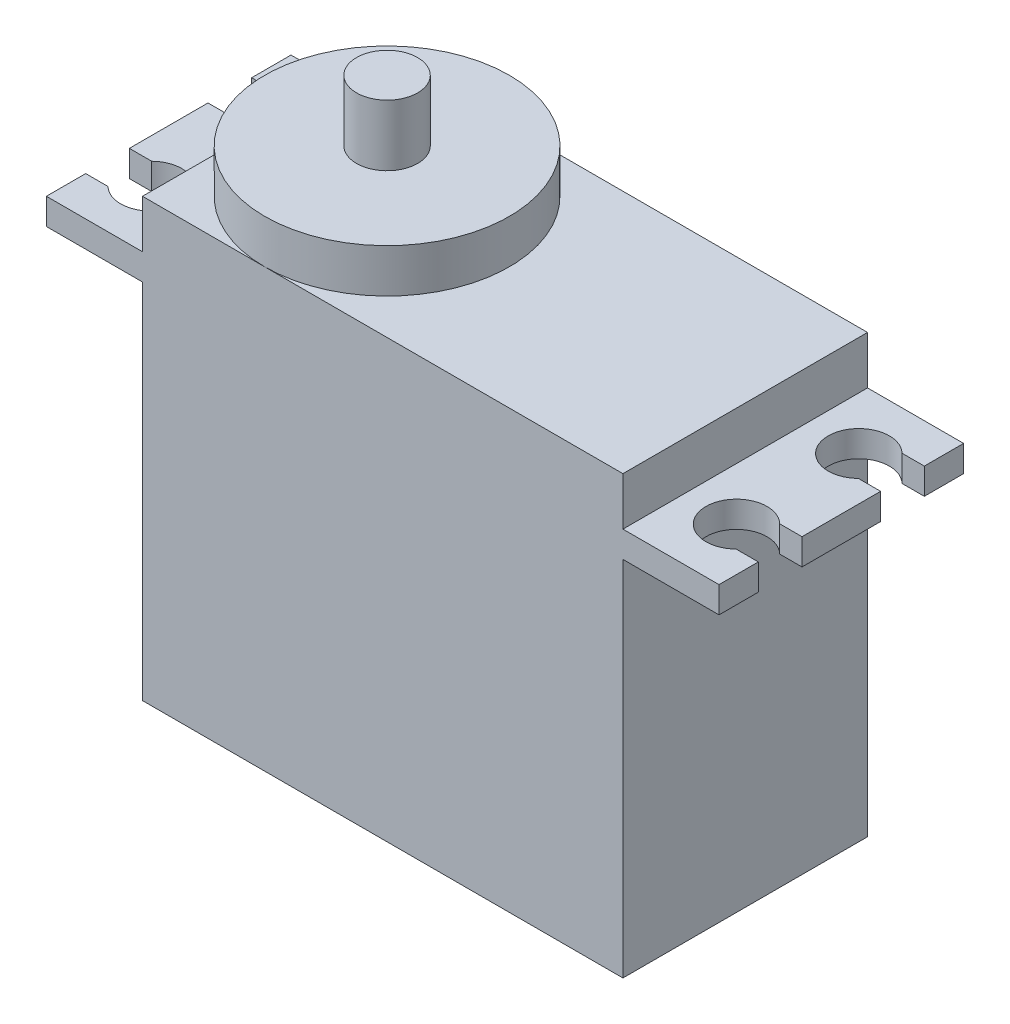
SolidWorks part; units mm, degrees
ref_plane "Front Plane" through (0, 0, 0) normal (0, 0, 1) x (1, 0, 0)
ref_plane "Top Plane" through (0, 0, 0) normal (0, 1, 0) x (1, 0, 0)
ref_plane "Right Plane" through (0, 0, 0) normal (1, 0, 0) x (0, 0, -1)
sketch "Sketch1" plane through (0, 0, 0) normal (0, 1, 0) x (1, 0, 0)
  line L1 (27.5, -14) -> (-27.5, -14)
  line L2 (27.5, -14) -> (27.5, 14)
  line L3 (27.5, 14) -> (-27.5, 14)
  line L4 (-27.5, -14) -> (-27.5, 14)
  line L5 (27.5, -14) -> (-27.5, 14) construction
  line L6 (27.5, 14) -> (-27.5, -14) construction
  point P0 (0, 0)
  dimension "D1" = 55
  dimension "D2" = 28
extrude "Boss-Extrude1" add sketch "Sketch1" along normal blind 50 contours L3 L4 L1 L2
sketch "Sketch2" plane through (0, 50, 0) normal (0, 1, 0) x (1, 0, 0)
  line L0 (-27.5, 0) -> (27.5, 0) construction
  line L1 (27.5, 14) -> (-27.5, 14) construction
  line L2 (-27.5, -14) -> (-27.5, 14) construction
  circle A0 centre (-13.5, 0) radius 14
extrude "Boss-Extrude2" add sketch "Sketch2" along normal blind 5
sketch "Sketch3" plane through (0, 55, 0) normal (0, 1, 0) x (1, 0, 0)
  circle A0 centre (-13.5, 0) radius 3.5
  dimension "D1" = 7
extrude "Boss-Extrude3" add sketch "Sketch3" along normal blind 7
ref_plane "Plane1" through (0, 41.5, 0) normal (0, 1, 0) x (1, 0, 0)
sketch "Sketch4" plane through (0, 41.5, 0) normal (0, 1, 0) x (1, 0, 0)
  line L0 (-13.5, 14) -> (-27.5, 14) construction
  line L1 (27.5, 14) -> (38.5, 14)
  line L2 (27.5, 14) -> (27.5, -14)
  line L3 (27.5, -14) -> (38.5, -14)
  line L4 (38.5, 14) -> (38.5, -14)
  line L5 (-27.5, -14) -> (-38.5, -14)
  line L6 (-27.5, -14) -> (-27.5, 14)
  line L7 (-27.5, 14) -> (-38.5, 14)
  line L8 (-38.5, -14) -> (-38.5, 14)
  line L9 (27.5, -14) -> (27.5, 14) construction
  dimension "D1" = 11
extrude "Boss-Extrude4" add sketch "Sketch4" along normal blind 3
sketch "Sketch5" plane through (0, 41.5, 0) normal (0, 1, 0) x (1, 0, 0)
  line L0 (35.9495, 4.5) -> (38.5, 4.5)
  line L1 (38.5, -14) -> (38.5, 14) construction
  line L2 (35.9495, 9.5) -> (38.5, 9.5)
  line L3 (38.5, 9.5) -> (38.5, 4.5)
  line L4 (-34.1, 0) -> (34.1, 0) construction
  line L5 (0, 21.7194) -> (0, -27.3299) construction
  line L6 (0, -15.4001) -> (0, 15.4001) construction
  line L7 (-51.3445, 0) -> (60.4403, 0) construction
  line L8 (38.5, -9.5) -> (38.5, -4.5)
  line L9 (35.9495, -9.5) -> (38.5, -9.5)
  line L10 (35.9495, -4.5) -> (38.5, -4.5)
  line L11 (-35.9495, -4.5) -> (-38.5, -4.5)
  line L12 (-35.9495, -9.5) -> (-38.5, -9.5)
  line L13 (-38.5, -9.5) -> (-38.5, -4.5)
  line L14 (-38.5, 9.5) -> (-38.5, 4.5)
  line L15 (-35.9495, 9.5) -> (-38.5, 9.5)
  line L16 (-35.9495, 4.5) -> (-38.5, 4.5)
  arc A0 (35.9495, 9.5) -> (35.9495, 4.5) centre (33.5, 7) ccw
  arc A1 (35.9495, -9.5) -> (35.9495, -4.5) centre (33.5, -7) cw
  arc A2 (-35.9495, -9.5) -> (-35.9495, -4.5) centre (-33.5, -7) ccw
  arc A3 (-35.9495, 9.5) -> (-35.9495, 4.5) centre (-33.5, 7) cw
  dimension "D1" = 3.5
  dimension "D4" = 5
  dimension "D2" = 7
  dimension "D3" = 5
extrude "Cut-Extrude1" cut sketch "Sketch5" along normal blind 3
